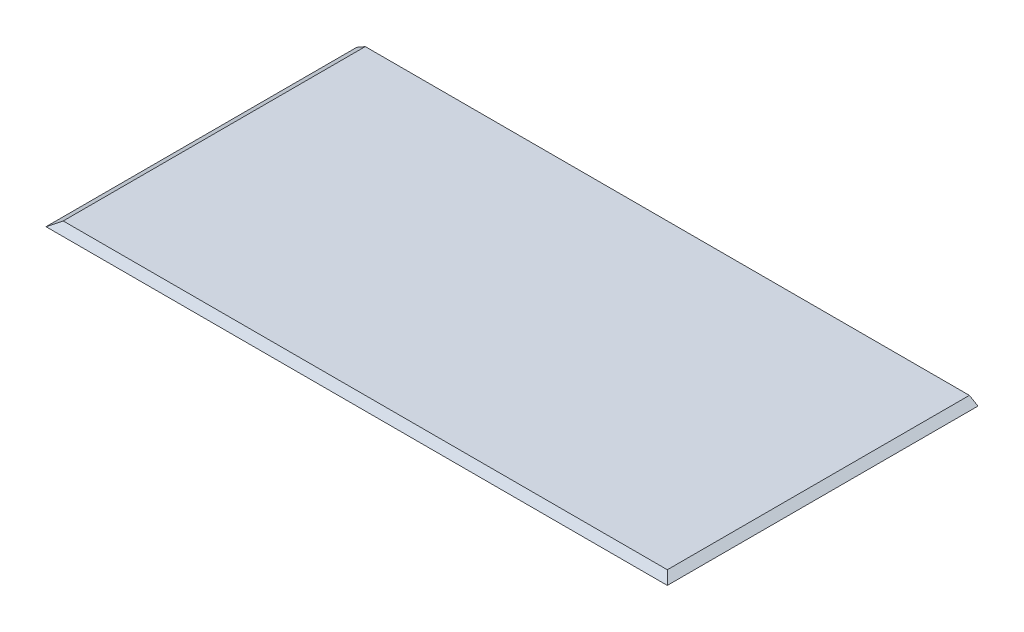
SolidWorks part; units mm, degrees
ref_plane "前视基准面" through (0, 0, 0) normal (0, 0, 1) x (1, 0, 0)
ref_plane "上视基准面" through (0, 0, 0) normal (0, 1, 0) x (1, 0, 0)
ref_plane "右视基准面" through (0, 0, 0) normal (1, 0, 0) x (0, 0, -1)
sketch "草图1" plane through (0, 0, 0) normal (0, 1, 0) x (1, 0, 0)
  line L1 (-125, -125) -> (125, -125)
  line L2 (-125, -125) -> (-125, 125)
  line L3 (-125, 125) -> (125, 125)
  line L4 (125, -125) -> (125, 125)
  line L5 (-125, -125) -> (125, 125) construction
  line L6 (-125, 125) -> (125, -125) construction
  point P0 (0, 0)
  dimension "D1" = 250
  dimension "D2" = 250
extrude "凸台-拉伸1" add sketch "草图1" along normal blind 2
sketch "草图2" plane through (0, 2, 0) normal (0, 1, 0) x (1, 0, 0)
  line L0 (-125, 0) -> (125, 0)
  line L4 (125, -125) -> (125, 125)
  line L5 (125, 125) -> (-125, 125)
  line L6 (-125, 125) -> (-125, -125)
  line L7 (-125, -125) -> (125, -125)
  line L8 (125, -125) -> (125, 0)
  line L10 (-125, 0) -> (-125, -125)
  line L11 (-125, -125) -> (125, -125)
  dimension "D1" = 0
extrude "切除-拉伸1" cut sketch "草图2" against normal up to surface (2 mm away) up to face at (0, 0, 0)
sketch "草图5" plane through (0, 0, 0) normal (0, -1, 0) x (1, 0, 0)
  line L0 (-0.2534, 0.2967) -> (-0.2534, -174.2192)
  line L1 (-125.2534, 0.2967) -> (124.7466, 0.2967)
  line L2 (-125.2534, 0.2967) -> (-125.2534, -124.7033)
  line L3 (-125.2534, -124.7033) -> (124.7466, -124.7033)
  line L4 (124.7466, 0.2967) -> (124.7466, -124.7033)
  line L5 (-125.2534, 0.2967) -> (-105.2534, 0.2967)
  line L6 (-125.2534, 0.2967) -> (-125.2534, -19.7033)
  line L7 (-125.2534, -19.7033) -> (-105.2534, -19.7033)
  line L8 (-105.2534, 0.2967) -> (-105.2534, -19.7033)
  line L9 (-125.2534, -124.7033) -> (-105.2534, -124.7033)
  line L10 (-125.2534, -124.7033) -> (-125.2534, -104.7033)
  line L11 (-125.2534, -104.7033) -> (-105.2534, -104.7033)
  line L12 (-105.2534, -124.7033) -> (-105.2534, -104.7033)
  line L13 (-110.2534, -14.7033) -> (-100.2534, -14.7033)
  line L14 (-110.2534, -14.7033) -> (-110.2534, -24.7033)
  line L15 (-110.2534, -24.7033) -> (-100.2534, -24.7033)
  line L16 (-100.2534, -14.7033) -> (-100.2534, -24.7033)
  line L17 (-110.2534, -14.7033) -> (-100.2534, -24.7033) construction
  line L18 (-110.2534, -24.7033) -> (-100.2534, -14.7033) construction
  line L19 (-110.2534, -99.7033) -> (-100.2534, -99.7033)
  line L20 (-110.2534, -99.7033) -> (-110.2534, -109.7033)
  line L21 (-110.2534, -109.7033) -> (-100.2534, -109.7033)
  line L22 (-100.2534, -99.7033) -> (-100.2534, -109.7033)
  line L23 (-110.2534, -99.7033) -> (-100.2534, -109.7033) construction
  line L24 (-110.2534, -109.7033) -> (-100.2534, -99.7033) construction
  line L25 (112.2466, -112.2033) -> (97.2466, -97.2033) construction
  line L26 (112.2466, -97.2033) -> (97.2466, -112.2033) construction
  line L27 (114.7466, -29.7033) -> (94.7466, -9.7033) construction
  line L28 (114.7466, -9.7033) -> (94.7466, -29.7033) construction
  line L29 (-115.2534, -9.7033) -> (-95.2534, -9.7033)
  line L30 (-115.2534, -9.7033) -> (-115.2534, -29.7033)
  line L31 (-115.2534, -29.7033) -> (-95.2534, -29.7033)
  line L32 (-95.2534, -9.7033) -> (-95.2534, -29.7033)
  line L33 (-115.2534, -9.7033) -> (-95.2534, -29.7033) construction
  line L34 (-115.2534, -29.7033) -> (-95.2534, -9.7033) construction
  line L35 (-112.7534, -97.2033) -> (-97.7534, -97.2033)
  line L36 (-112.7534, -97.2033) -> (-112.7534, -112.2033)
  line L37 (-112.7534, -112.2033) -> (-97.7534, -112.2033)
  line L38 (-97.7534, -97.2033) -> (-97.7534, -112.2033)
  line L39 (-112.7534, -97.2033) -> (-97.7534, -112.2033) construction
  line L40 (-112.7534, -112.2033) -> (-97.7534, -97.2033) construction
  line L41 (109.7466, -109.7033) -> (99.7466, -99.7033) construction
  line L42 (109.7466, -99.7033) -> (99.7466, -109.7033) construction
  line L43 (109.7466, -24.7033) -> (99.7466, -14.7033) construction
  line L44 (109.7466, -14.7033) -> (99.7466, -24.7033) construction
  line L45 (97.2466, -97.2033) -> (97.2466, -112.2033)
  line L46 (112.2466, -112.2033) -> (97.2466, -112.2033)
  line L47 (112.2466, -97.2033) -> (112.2466, -112.2033)
  line L48 (112.2466, -97.2033) -> (97.2466, -97.2033)
  line L49 (94.7466, -9.7033) -> (94.7466, -29.7033)
  line L50 (114.7466, -29.7033) -> (94.7466, -29.7033)
  line L51 (114.7466, -9.7033) -> (114.7466, -29.7033)
  line L52 (114.7466, -9.7033) -> (94.7466, -9.7033)
  line L53 (99.7466, -99.7033) -> (99.7466, -109.7033)
  line L54 (109.7466, -109.7033) -> (99.7466, -109.7033)
  line L55 (109.7466, -99.7033) -> (109.7466, -109.7033)
  line L56 (109.7466, -99.7033) -> (99.7466, -99.7033)
  line L57 (99.7466, -14.7033) -> (99.7466, -24.7033)
  line L58 (109.7466, -24.7033) -> (99.7466, -24.7033)
  line L59 (109.7466, -14.7033) -> (109.7466, -24.7033)
  line L60 (109.7466, -14.7033) -> (99.7466, -14.7033)
  line L61 (104.7466, -124.7033) -> (104.7466, -104.7033)
  line L62 (124.7466, -104.7033) -> (104.7466, -104.7033)
  line L63 (124.7466, -124.7033) -> (124.7466, -104.7033)
  line L64 (124.7466, -124.7033) -> (104.7466, -124.7033)
  line L65 (104.7466, 0.2967) -> (104.7466, -19.7033)
  line L66 (124.7466, -19.7033) -> (104.7466, -19.7033)
  line L67 (124.7466, 0.2967) -> (124.7466, -19.7033)
  line L68 (124.7466, 0.2967) -> (104.7466, 0.2967)
  line L69 (124.7466, 0.2967) -> (124.7466, -124.7033)
sketch "草图6" plane through (0, 0, 0) normal (0, -1, 0) x (1, 0, 0)
  line L1 (-110.2534, -14.7033) -> (-100.2534, -14.7033)
  line L2 (-110.2534, -14.7033) -> (-110.2534, -24.7033)
  line L3 (-110.2534, -24.7033) -> (-100.2534, -24.7033)
  line L4 (-100.2534, -14.7033) -> (-100.2534, -24.7033)
  line L5 (-110.2534, -99.7033) -> (-100.2534, -99.7033)
  line L6 (-110.2534, -99.7033) -> (-110.2534, -109.7033)
  line L7 (-110.2534, -109.7033) -> (-100.2534, -109.7033)
  line L8 (-100.2534, -99.7033) -> (-100.2534, -109.7033)
  line L9 (99.7466, -14.7033) -> (109.7466, -14.7033)
  line L10 (99.7466, -14.7033) -> (99.7466, -24.7033)
  line L11 (99.7466, -24.7033) -> (109.7466, -24.7033)
  line L12 (109.7466, -14.7033) -> (109.7466, -24.7033)
  line L13 (99.7466, -99.7033) -> (109.7466, -99.7033)
  line L14 (99.7466, -99.7033) -> (99.7466, -109.7033)
  line L15 (99.7466, -109.7033) -> (109.7466, -109.7033)
  line L16 (109.7466, -99.7033) -> (109.7466, -109.7033)
extrude "凸台-拉伸3" add sketch "草图6" along normal blind 10
sketch "草图9" plane through (0, 0, -125) normal (0, 0, -1) x (-1, 0, 0)
  line L0 (-125, 0) -> (-125, 2)
  line L1 (-125, 2) -> (-121.5359, 2)
  line L2 (-125, 2) -> (125, 2) construction
  line L3 (-121.5359, 2) -> (-125, 0)
  line L5 (125, 2) -> (121.5359, 2)
  line L6 (125, 0) -> (125, 2)
  line L7 (121.5359, 2) -> (125, 0)
  dimension "D1" = 30
extrude "切除-拉伸2" cut sketch "草图9" against normal up to surface (125 mm away) up to face at (0, 1, 0)
sketch "草图11" plane through (0, 0, 0) normal (1, 0, 0) x (0, 0, -1)
  line L3 (0, 2) -> (125, 2) construction
  line L7 (0, 2) -> (0, 0)
  line L8 (0, 0) -> (3.4641, 2)
  line L9 (3.4641, 2) -> (0, 2)
  dimension "D1" = 30
extrude "切除-拉伸3" cut sketch "草图11" against normal through all and the other way through all
